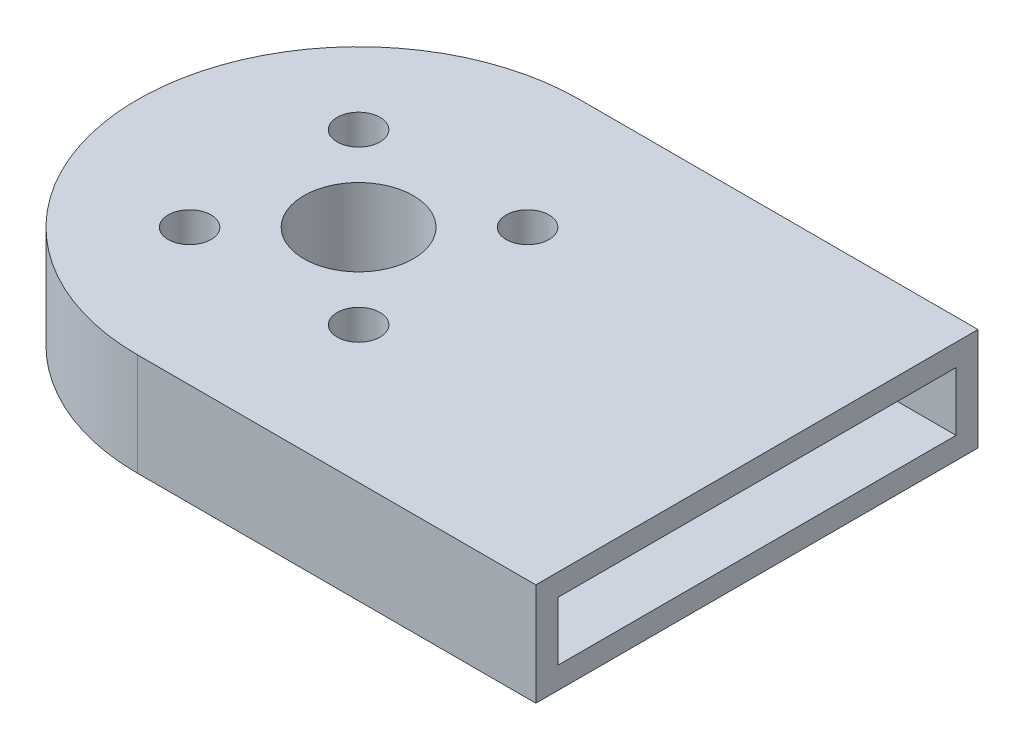
SolidWorks part; units mm, degrees
ref_plane "Front Plane" through (0, 0, 0) normal (0, 0, 1) x (1, 0, 0)
ref_plane "Top Plane" through (0, 0, 0) normal (0, 1, 0) x (1, 0, 0)
ref_plane "Right Plane" through (0, 0, 0) normal (1, 0, 0) x (0, 0, -1)
sketch "Sketch2" plane through (0, 0, 0) normal (0, 1, 0) x (1, 0, 0)
  line L0 (-4.2426, 4.2426) -> (4.2426, -4.2426) construction
  line L1 (4.2426, 4.2426) -> (-4.2426, -4.2426) construction
  line L2 (0, 7.5828) -> (0, -11.9719) construction
  line L3 (0, 11.1) -> (20, 11.1)
  line L4 (20, 11.1) -> (20, -11.1)
  line L5 (20, -11.1) -> (0, -11.1)
  arc A0 (0, 11.1) -> (0, -11.1) centre (0, 0) ccw
  circle A1 centre (-4.2426, 4.2426) radius 1.075
  circle A2 centre (4.2426, 4.2426) radius 1.075
  circle A3 centre (-4.2426, -4.2426) radius 1.075
  circle A4 centre (4.2426, -4.2426) radius 1.075
  circle A5 centre (0, 0) radius 2.75
  point P11 (0, 0)
  point P12 (0, 0)
  dimension "D1" = 22.2
  dimension "D2" = 2.15
  dimension "D3" = 2.15
  dimension "D4" = 2.15
  dimension "D5" = 2.15
  dimension "D6" = 2.15
  dimension "D11" = 5.5
  dimension "D7" = 12
  dimension "D8" = 12
  dimension "D9" = 45
  dimension "D10" = 45
  dimension "D12" = 20
extrude "Boss-Extrude1" add sketch "Sketch2" along normal blind 5.15
sketch "Sketch3" plane through (0, 5.15, 0) normal (0, 1, 0) x (1, 0, 0)
  line L0 (0, 11.1) -> (16.3154, 11.1)
  line L1 (0, -11.1) -> (16.3154, -11.1)
  line L2 (16.3154, 11.1) -> (16.3154, -11.1)
  line L6 (0, -11.1) -> (20, -11.1)
  line L7 (0, -11.1) -> (20, -11.1)
  line L8 (20, -11.1) -> (20, 11.1)
  line L9 (20, -11.1) -> (20, 11.1)
  line L10 (20, 11.1) -> (0, 11.1)
  line L11 (20, 11.1) -> (0, 11.1)
  circle A0 centre (0, 0) radius 11.1 construction
  arc A2 (0, 11.1) -> (0, -11.1) centre (0, 0) ccw
  arc A3 (0, 11.1) -> (0, -11.1) centre (0, 0) ccw
  dimension "D1" = 0
shell "Shell1" thickness 1.1
